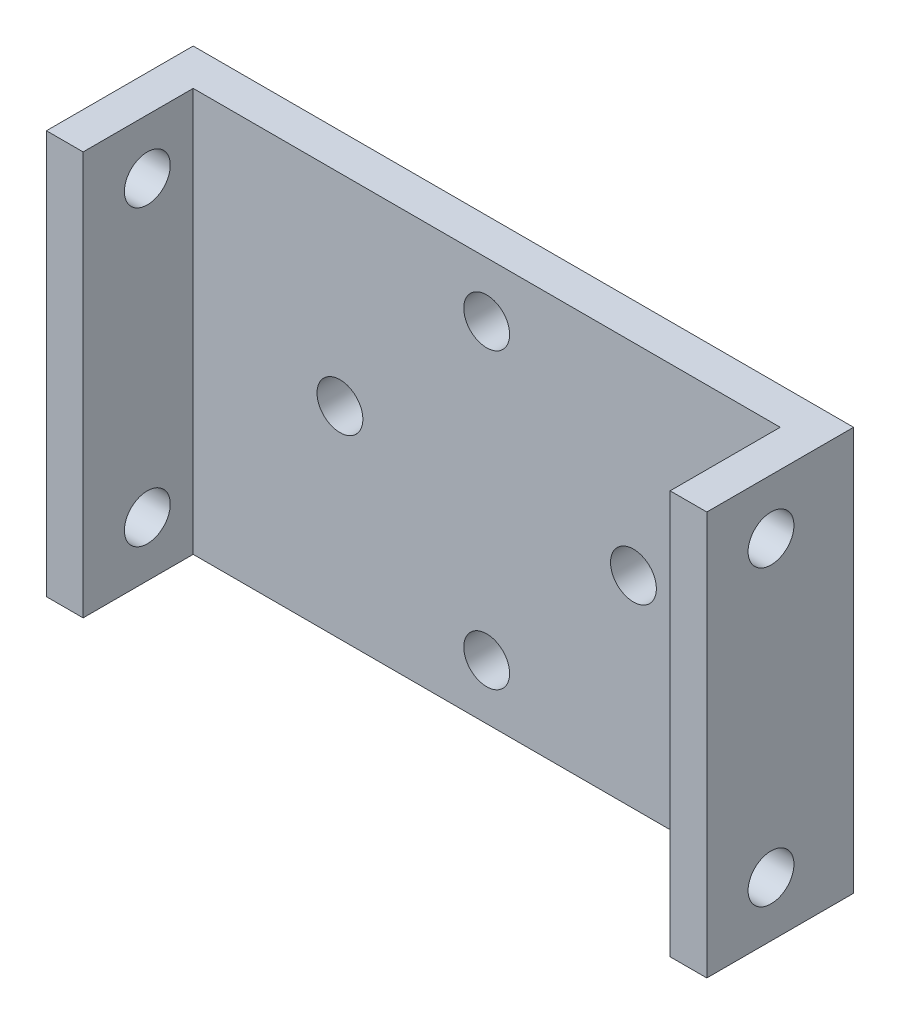
SolidWorks part; units mm, degrees
ref_plane "Plano frontal" through (0, 0, 0) normal (0, 0, 1) x (1, 0, 0)
ref_plane "Plano superior" through (0, 0, 0) normal (0, 1, 0) x (1, 0, 0)
ref_plane "Plano direito" through (0, 0, 0) normal (1, 0, 0) x (0, 0, -1)
sketch "Esboço1" plane through (0, 0, 0) normal (0, 0, 1) x (1, 0, 0)
  line L1 (-18, -11) -> (18, -11)
  line L2 (-18, -11) -> (-18, 11)
  line L3 (-18, 11) -> (18, 11)
  line L4 (18, -11) -> (18, 11)
  line L5 (-18, -11) -> (18, 11) construction
  line L6 (-18, 11) -> (18, -11) construction
  circle A0 centre (0, 0) radius 8 construction
  circle A1 centre (0, 8) radius 1.25
  circle A2 centre (8, 0) radius 1.25
  circle A3 centre (0, -8) radius 1.25
  circle A4 centre (-8, 0) radius 1.25
  point P0 (0, 0)
  point P19 (0, 0)
  dimension "D3" = 4
  dimension "D1" = 36
  dimension "D2" = 22
extrude "Ressalto-extrusão1" add sketch "Esboço1" along normal blind 2
sketch "Esboço2" plane through (0, 0, 2) normal (0, 0, 1) x (1, 0, 0)
  line L0 (-18, -11) -> (18, -11) construction
  line L1 (-18, 11) -> (-16, 11)
  line L2 (-18, 11) -> (-18, -11)
  line L3 (-18, -11) -> (-16, -11)
  line L4 (-16, 11) -> (-16, -11)
  line L5 (0, 0) -> (0, 11) construction
  line L6 (18, 11) -> (-18, 11) construction
  line L7 (18, -11) -> (16, -11)
  line L8 (16, 11) -> (16, -11)
  line L9 (18, 11) -> (16, 11)
  line L10 (18, 11) -> (18, -11)
  dimension "D1" = 2
extrude "Ressalto-extrusão2" add sketch "Esboço2" along normal blind 6
sketch "Esboço3" plane through (-18, 0, 0) normal (-1, 0, 0) x (0, 0, 1)
  line L0 (0, 0) -> (8, 0) construction
  line L1 (0, 11) -> (0, -11) construction
  line L2 (8, 11) -> (8, -11) construction
  circle A0 centre (4.5, 8) radius 1.25
  circle A1 centre (4.5, -8) radius 1.25
  dimension "D1" = 2.5
  dimension "D2" = 8
  dimension "D3" = 4.5
extrude "Corte-extrusão1" cut sketch "Esboço3" against normal up to surface (36 mm away) up to face at (18, 0, 4)
